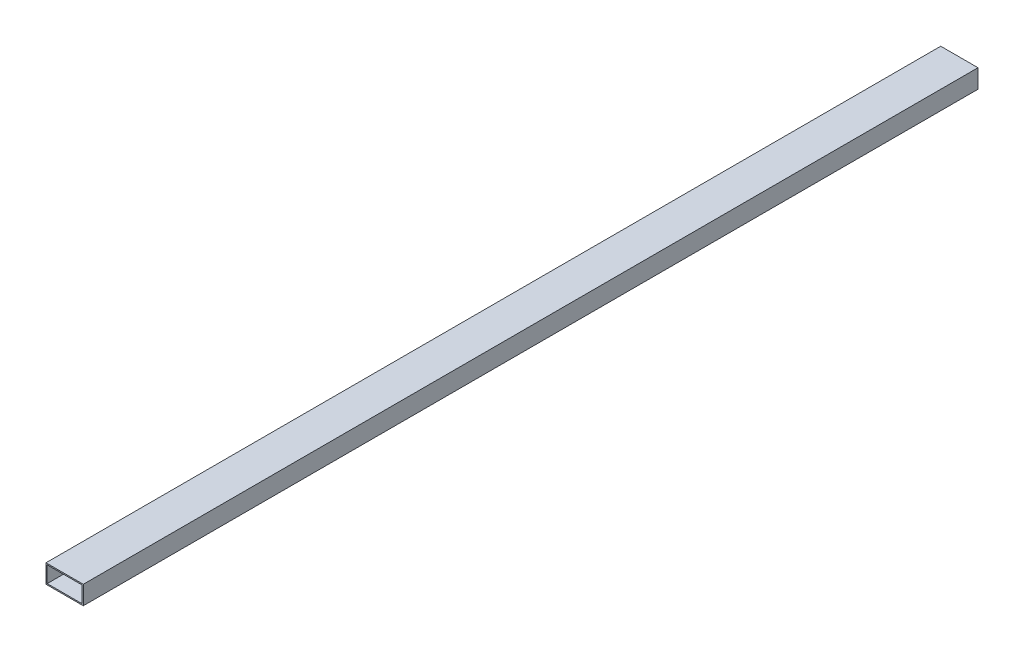
SolidWorks part; units mm, degrees
material "6061 Alloy"
ref_plane "Front Plane" through (0, 0, 0) normal (0, 0, 1) x (1, 0, 0)
ref_plane "Top Plane" through (0, 0, 0) normal (0, 1, 0) x (1, 0, 0)
ref_plane "Right Plane" through (0, 0, 0) normal (1, 0, 0) x (0, 0, -1)
sketch "Sketch1" plane through (0, 0, 0) normal (0, 0, 1) x (1, 0, 0)
  line L1 (0, 0) -> (50.8, 0)
  line L2 (0, 0) -> (0, 25.4)
  line L3 (0, 25.4) -> (50.8, 25.4)
  line L4 (50.8, 0) -> (50.8, 25.4)
  line L5 (1.651, 1.651) -> (49.149, 1.651)
  line L6 (1.651, 1.651) -> (1.651, 23.749)
  line L7 (1.651, 23.749) -> (49.149, 23.749)
  line L8 (49.149, 1.651) -> (49.149, 23.749)
  dimension "D1" = 50.8
  dimension "D2" = 25.4
  dimension "D3" = 1.651
  dimension "D4" = 1.651
  dimension "D5" = 1.651
  dimension "D6" = 1.651
extrude "Boss-Extrude1" add sketch "Sketch1" along normal blind 1219.2
